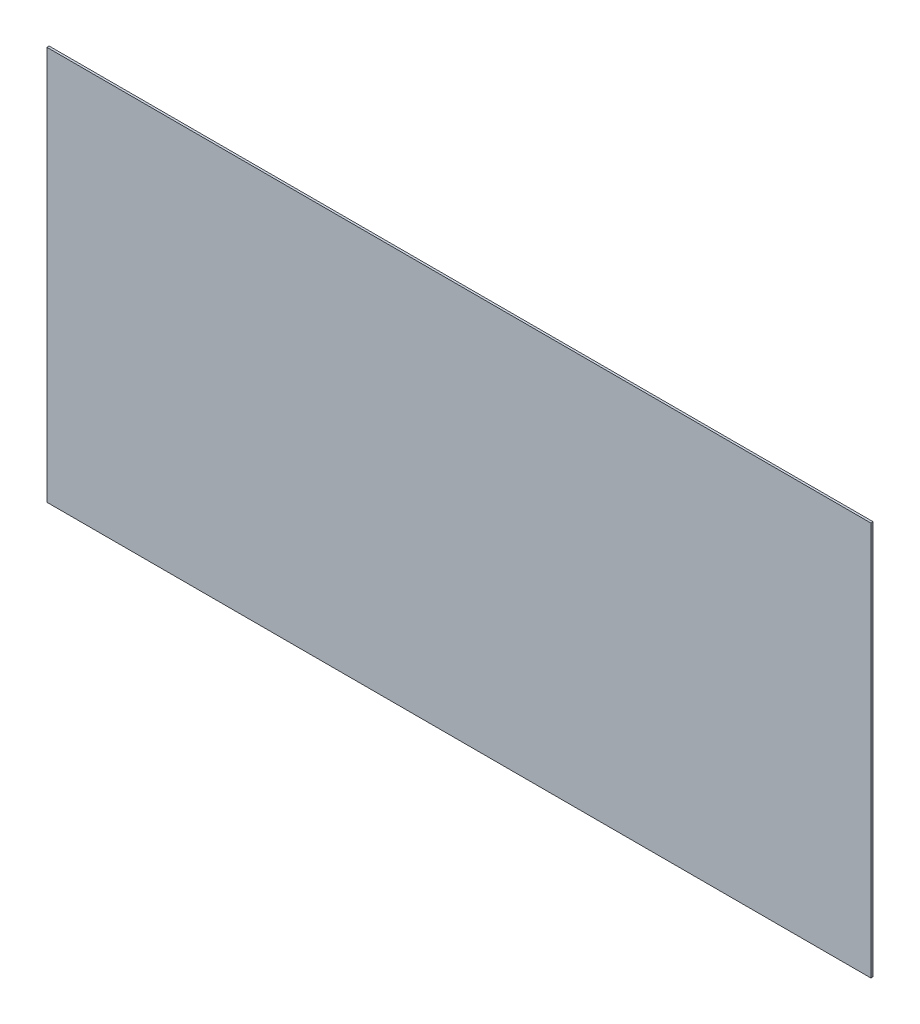
SolidWorks part; units mm, degrees
material "6061 Alloy"
ref_plane "Front Plane" through (0, 0, 0) normal (0, 0, 1) x (1, 0, 0)
ref_plane "Top Plane" through (0, 0, 0) normal (0, 1, 0) x (1, 0, 0)
ref_plane "Right Plane" through (0, 0, 0) normal (1, 0, 0) x (0, 0, -1)
sketch "Sketch1" plane through (0, 0, 0) normal (0, 0, 1) x (1, 0, 0)
  line L1 (0, 0) -> (584.2, 0)
  line L2 (0, 0) -> (0, 279.4)
  line L3 (0, 279.4) -> (584.2, 279.4)
  line L4 (584.2, 0) -> (584.2, 279.4)
  dimension "D1" = 584.2
  dimension "D2" = 279.4
extrude "Boss-Extrude1" add sketch "Sketch1" along normal blind 1.5875
